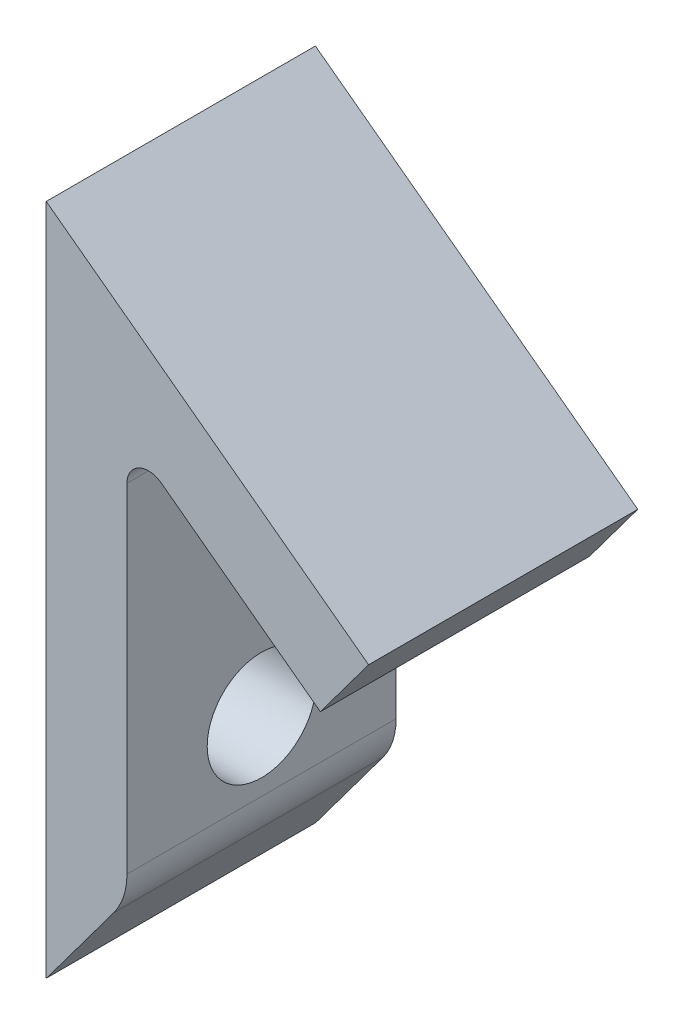
SolidWorks part; units mm, degrees
ref_plane "Front Plane" through (0, 0, 0) normal (0, 0, 1) x (1, 0, 0)
ref_plane "Top Plane" through (0, 0, 0) normal (0, 1, 0) x (1, 0, 0)
ref_plane "Right Plane" through (0, 0, 0) normal (1, 0, 0) x (0, 0, -1)
sketch "Sketch2" plane through (0, 0, 0) normal (0, 0, 1) x (1, 0, 0)
  line L0 (0, 0) -> (0, 25)
  line L1 (0, 25) -> (11.9763, 16.0802)
  line L2 (11.9763, 16.0802) -> (0, 0)
  line L3 (11.9763, 16.0802) -> (10.1844, 13.6742)
  line L4 (11.9763, 16.0802) -> (1.1319, 24.157)
  line L5 (10.1844, 13.6742) -> (-0.6601, 21.751)
  line L6 (1.1319, 24.157) -> (-0.6601, 21.751)
  line L7 (0, 25) -> (3, 25)
  line L8 (0, 25) -> (0, 0.0224)
  line L9 (3, 25) -> (3, 0.0224)
  line L10 (0, 0.0224) -> (3, 0.0224)
  dimension "D1" = 25
  dimension "D2" = 3
  dimension "D3" = 3
extrude "Boss-Extrude1" add sketch "Sketch2" along normal blind 10 contours L0 L10 L2 L9 L5 | L9 L1 L6 L0 L5 | L4 L9 L5 L2 | L6 L1 L0
fillet "Fillet1" radius 0.8 1 edges at (3, 19.025, 5)
fillet "Fillet2" radius 2.5 1 edges at (3, 4.028, 5)
sketch "Sketch6" plane through (0, 0, 0) normal (-1, 0, 0) x (0, 0, 1)
  line L0 (5, 25) -> (5, 0.0224) construction
  line L1 (10, 25) -> (0, 25) construction
  line L2 (10, 0.0224) -> (0, 0.0224) construction
  circle A0 centre (5, 15.4766) radius 2.02
  circle A1 centre (5, 7.4766) radius 2.02
  point P9 (0, 0)
  point P11 (0, 0)
  dimension "D1" = 4.04
  dimension "D3" = 8
  dimension "D2" = 2
extrude "Cut-Extrude1" cut sketch "Sketch6" against normal blind 4
